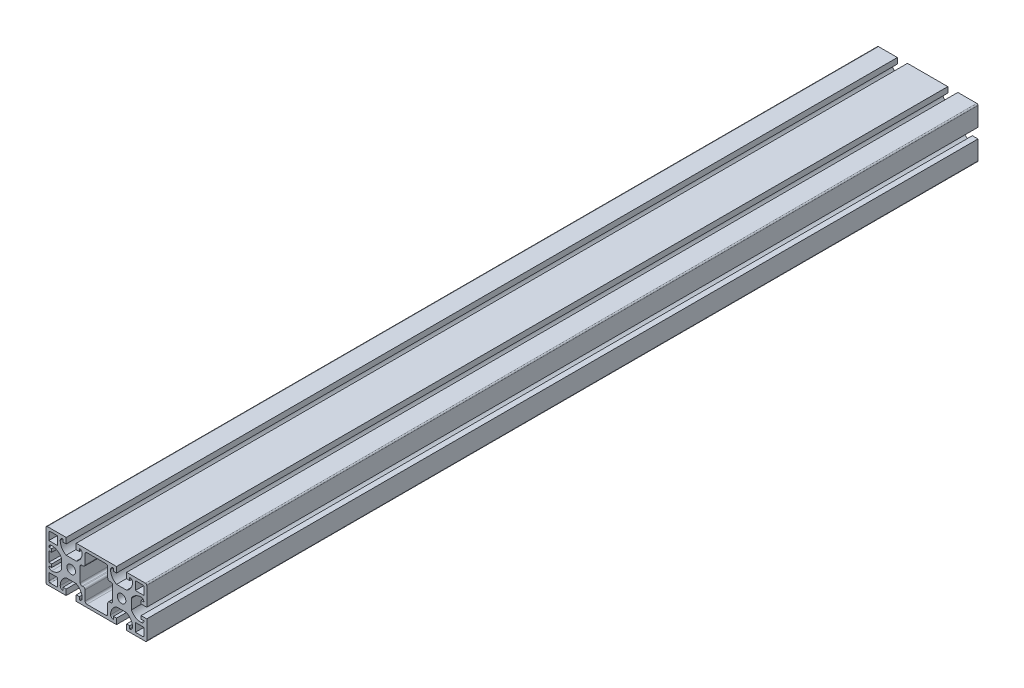
SolidWorks part; units mm, degrees
material "3.0255 (EN-AW 1350A)"
ref_plane "Płaszczyzna przednia" through (0, 0, 0) normal (0, 0, 1) x (1, 0, 0)
ref_plane "Płaszczyzna górna" through (0, 0, 0) normal (0, 1, 0) x (1, 0, 0)
ref_plane "Płaszczyzna prawa" through (0, 0, 0) normal (1, 0, 0) x (0, 0, -1)
sketch "Szkic1" plane through (0, 0, 0) normal (0, 0, 1) x (1, 0, 0)
  line L0 (0, 20) -> (0, -20) construction
  line L1 (-51.8865, 0) -> (40, 0) construction
  line L4 (-40, -19) -> (-40, 19)
  line L7 (-40, -20) -> (0, 0) construction
  line L8 (-40, 20) -> (40, -20) construction
  line L13 (20, 20) -> (20, 0) construction
  line L15 (24, 20) -> (24, 15.5)
  line L16 (24, 15.5) -> (26.4714, 15.5)
  line L21 (16, 15.5) -> (13.5286, 15.5)
  line L23 (16, 20) -> (13.5286, 20)
  line L24 (16, 20) -> (16, 15.5)
  line L25 (16, 7.75) -> (24, 7.75)
  line L26 (13.5286, 15.5) -> (13.5286, 17.75)
  line L27 (26.4714, 15.5) -> (26.4714, 17.75)
  line L28 (-24, 20) -> (-24, 15.5)
  line L29 (-26.4714, 15.5) -> (-26.4714, 17.75)
  line L30 (-24, 15.5) -> (-26.4714, 15.5)
  line L31 (-13.5286, 15.5) -> (-13.5286, 17.75)
  line L32 (-16, 15.5) -> (-13.5286, 15.5)
  line L33 (-16, 20) -> (-16, 15.5)
  line L34 (-16, 7.75) -> (-24, 7.75)
  line L35 (20, -20) -> (20, 0) construction
  line L36 (-40, -20) -> (0, 0) construction
  line L37 (-40, 20) -> (40, -20) construction
  line L38 (30.9714, -17.75) -> (36.75, -17.75)
  line L39 (-16, -7.75) -> (-24, -7.75)
  line L40 (-16, -20) -> (-16, -15.5)
  line L41 (-16, -15.5) -> (-13.5286, -15.5)
  line L42 (-13.5286, -15.5) -> (-13.5286, -17.75)
  line L43 (-24, -15.5) -> (-26.4714, -15.5)
  line L44 (-26.4714, -15.5) -> (-26.4714, -17.75)
  line L45 (-24, -20) -> (-24, -15.5)
  line L46 (26.4714, -15.5) -> (26.4714, -17.75)
  line L47 (13.5286, -15.5) -> (13.5286, -17.75)
  line L48 (16, -7.75) -> (24, -7.75)
  line L49 (16, -20) -> (16, -15.5)
  line L50 (16, -15.5) -> (13.5286, -15.5)
  line L51 (24, -15.5) -> (26.4714, -15.5)
  line L52 (24, -20) -> (24, -15.5)
  line L53 (40, -20) -> (0, 20) construction
  line L54 (35.5, 6.4714) -> (37.75, 6.4714)
  line L55 (35.5, 4) -> (35.5, 6.4714)
  line L56 (40, 4) -> (35.5, 4)
  line L57 (40, -4) -> (35.5, -4)
  line L58 (35.5, -4) -> (35.5, -6.4714)
  line L59 (35.5, -6.4714) -> (37.75, -6.4714)
  line L60 (27.75, 4) -> (27.75, -4)
  line L61 (-35.5, -6.4714) -> (-37.75, -6.4714)
  line L62 (-37.75, -4) -> (-35.5, -4)
  line L63 (-35.5, -4) -> (-35.5, -6.4714)
  line L64 (-35.5, 4) -> (-35.5, 6.4714)
  line L65 (-35.5, 6.4714) -> (-37.75, 6.4714)
  line L66 (-37.75, 4) -> (-35.5, 4)
  line L67 (-27.75, 4) -> (-27.75, -4)
  line L68 (-37.75, 4) -> (-37.75, -4)
  line L69 (40, -4) -> (40, -19)
  line L70 (40, 19) -> (40, 4)
  line L71 (-39, -20) -> (-24, -20)
  line L72 (-16, -20) -> (16, -20)
  line L73 (24, -20) -> (39, -20)
  line L74 (13.5286, 20) -> (-16, 20)
  line L75 (-24, 20) -> (-39, 20)
  line L76 (24, 20) -> (39, 20)
  line L77 (10.5286, 7.0902) -> (11.4095, 7.0902)
  line L78 (-7.5286, -17.75) -> (7.5286, -17.75)
  line L79 (-9.0286, -16.25) -> (-9.0286, -8.5902)
  line L80 (-7.5286, 17.75) -> (7.5286, 17.75)
  line L81 (9.0286, -16.25) -> (9.0286, -8.5902)
  line L82 (-9.0286, -17.75) -> (9.0286, 17.75) construction
  line L83 (-9.0286, 17.75) -> (9.0286, -17.75) construction
  line L84 (-11.4095, -7.0902) -> (-10.5286, -7.0902)
  line L85 (-12.9095, -5.5902) -> (-12.9095, 5.5902)
  line L86 (-11.4095, 7.0902) -> (-10.5286, 7.0902)
  line L87 (12.9095, -5.5902) -> (12.9095, 5.5902)
  line L88 (-12.9095, -7.0902) -> (0, 0) construction
  line L89 (-12.9095, 7.0902) -> (12.9095, -7.0902) construction
  line L90 (-9.0286, 8.5902) -> (-9.0286, 16.25)
  line L91 (-9.0286, 4.5143) -> (-9.0286, 4.9587)
  line L92 (-9.0286, -4.9587) -> (-9.0286, -4.5143)
  line L93 (9.0286, 8.5902) -> (9.0286, 16.25)
  line L94 (10.5286, -7.0902) -> (11.4095, -7.0902)
  line L96 (0, 0) -> (12.9095, 7.0902) construction
  line L98 (37.75, -10.9714) -> (37.75, -16.75)
  line L99 (30.9714, 10.9714) -> (37.75, 10.9714)
  line L100 (30.9714, 10.9714) -> (30.9714, 17.75)
  line L101 (30.9714, 17.75) -> (36.75, 17.75)
  line L102 (37.75, 10.9714) -> (37.75, 16.75)
  line L103 (30.9714, 10.9714) -> (37.75, 17.75) construction
  line L104 (30.9714, 17.75) -> (37.75, 10.9714) construction
  line L105 (30.9714, -10.9714) -> (37.75, -10.9714)
  line L106 (30.9714, -10.9714) -> (30.9714, -17.75)
  line L107 (-30.9714, -10.9714) -> (-30.9714, -17.75)
  line L108 (-30.9714, -10.9714) -> (-37.75, -10.9714)
  line L109 (-37.75, -10.9714) -> (-37.75, -16.75)
  line L110 (-30.9714, -17.75) -> (-36.75, -17.75)
  line L111 (-30.9714, 17.75) -> (-36.75, 17.75)
  line L112 (-37.75, 10.9714) -> (-37.75, 16.75)
  line L113 (-30.9714, 10.9714) -> (-37.75, 10.9714)
  line L114 (-30.9714, 10.9714) -> (-30.9714, 17.75)
  circle A0 centre (-20, 0) radius 3.4
  circle A1 centre (20, 0) radius 3.4
  arc A2 (26.4714, 17.75) -> (28.7214, 15.5) centre (26.4714, 15.5) cw
  arc A3 (28.7214, 15.5) -> (24, 7.75) centre (20, 15.5) cw
  arc A4 (13.5286, 17.75) -> (11.2786, 15.5) centre (13.5286, 15.5) ccw
  arc A5 (11.2786, 15.5) -> (16, 7.75) centre (20, 15.5) ccw
  arc A6 (-26.4714, 17.75) -> (-28.7214, 15.5) centre (-26.4714, 15.5) ccw
  arc A7 (-13.5286, 17.75) -> (-11.2786, 15.5) centre (-13.5286, 15.5) cw
  arc A8 (-11.2786, 15.5) -> (-16, 7.75) centre (-20, 15.5) cw
  arc A9 (-28.7214, 15.5) -> (-24, 7.75) centre (-20, 15.5) ccw
  arc A10 (-28.7214, -15.5) -> (-24, -7.75) centre (-20, -15.5) cw
  arc A11 (-11.2786, -15.5) -> (-16, -7.75) centre (-20, -15.5) ccw
  arc A12 (-13.5286, -17.75) -> (-11.2786, -15.5) centre (-13.5286, -15.5) ccw
  arc A13 (-26.4714, -17.75) -> (-28.7214, -15.5) centre (-26.4714, -15.5) cw
  arc A14 (11.2786, -15.5) -> (16, -7.75) centre (20, -15.5) cw
  arc A15 (13.5286, -17.75) -> (11.2786, -15.5) centre (13.5286, -15.5) cw
  arc A16 (28.7214, -15.5) -> (24, -7.75) centre (20, -15.5) ccw
  arc A17 (26.4714, -17.75) -> (28.7214, -15.5) centre (26.4714, -15.5) ccw
  arc A18 (35.5, 8.7214) -> (27.75, 4) centre (35.5, 0) ccw
  arc A19 (37.75, 6.4714) -> (35.5, 8.7214) centre (35.5, 6.4714) ccw
  arc A20 (37.75, -6.4714) -> (35.5, -8.7214) centre (35.5, -6.4714) cw
  arc A21 (35.5, -8.7214) -> (27.75, -4) centre (35.5, 0) cw
  arc A22 (-35.5, -8.7214) -> (-27.75, -4) centre (-35.5, 0) ccw
  arc A23 (-37.75, -6.4714) -> (-35.5, -8.7214) centre (-35.5, -6.4714) ccw
  arc A24 (-37.75, 6.4714) -> (-35.5, 8.7214) centre (-35.5, 6.4714) cw
  arc A25 (-35.5, 8.7214) -> (-27.75, 4) centre (-35.5, 0) cw
  arc A26 (-10.5286, 7.0902) -> (-9.0286, 8.5902) centre (-10.5286, 8.5902) ccw
  arc A27 (-9.0286, -8.5902) -> (-10.5286, -7.0902) centre (-10.5286, -8.5902) ccw
  arc A28 (11.4095, -7.0902) -> (12.9095, -5.5902) centre (11.4095, -5.5902) ccw
  arc A29 (9.0286, -8.5902) -> (10.5286, -7.0902) centre (10.5286, -8.5902) cw
  arc A30 (7.5286, -17.75) -> (9.0286, -16.25) centre (7.5286, -16.25) ccw
  arc A31 (-7.5286, -17.75) -> (-9.0286, -16.25) centre (-7.5286, -16.25) cw
  arc A32 (-11.4095, -7.0902) -> (-12.9095, -5.5902) centre (-11.4095, -5.5902) cw
  arc A33 (-12.9095, 5.5902) -> (-11.4095, 7.0902) centre (-11.4095, 5.5902) cw
  arc A34 (-9.0286, 16.25) -> (-7.5286, 17.75) centre (-7.5286, 16.25) cw
  arc A35 (7.5286, 17.75) -> (9.0286, 16.25) centre (7.5286, 16.25) cw
  arc A36 (11.4095, 7.0902) -> (12.9095, 5.5902) centre (11.4095, 5.5902) cw
  arc A37 (10.5286, 7.0902) -> (9.0286, 8.5902) centre (10.5286, 8.5902) cw
  arc A38 (-40, 19) -> (-39, 20) centre (-39, 19) cw
  arc A39 (-39, -20) -> (-40, -19) centre (-39, -19) cw
  arc A40 (39, -20) -> (40, -19) centre (39, -19) ccw
  arc A41 (39, 20) -> (40, 19) centre (39, 19) cw
  arc A42 (36.75, 17.75) -> (37.75, 16.75) centre (36.75, 16.75) cw
  arc A43 (36.75, -17.75) -> (37.75, -16.75) centre (36.75, -16.75) ccw
  arc A44 (-36.75, -17.75) -> (-37.75, -16.75) centre (-36.75, -16.75) cw
  arc A45 (-36.75, 17.75) -> (-37.75, 16.75) centre (-36.75, 16.75) ccw
  point P5 (0, 0)
  point P17 (0, 0)
  point P30 (24, 17.75)
  point P108 (0, 0)
  point P124 (-9.0286, 7.0902)
  point P132 (9.0286, -7.0902)
  point P156 (9.0286, 7.0902)
  point P161 (40, 20)
  point P162 (34.3607, 14.3607)
  dimension "D4" = 6.8
  dimension "D5" = 12.25
  dimension "D9" = 11
  dimension "D11" = 1.5
  dimension "D12" = 1
  dimension "D16" = 1
  dimension "D1" = 80
  dimension "D2" = 40
  dimension "D3" = 40
  dimension "D6" = 2.25
  dimension "D7" = 8
  dimension "D8" = 4.5
  dimension "D10" = 14.1804
  dimension "D13" = 2.25
  dimension "D14" = 2.25
  dimension "D15" = 2.25
extrude "Dodanie-wyciągnięcie1" add sketch "Szkic1" along normal blind 660 contours A20 A21 L60 A18 A19 L54 L55 L56 L70 L76 L15 L16 L27 A2 A3 L25 A5 A4 L26 L21 L24 L23 L74 L33 L32 L31 A7 A8 L34 A9 A6 L29 L30 L28 L75 L4 L71 L45 L43 L44 A13 A10 L39 A11 A12 L42 L41 L40 L72 L49 L50
